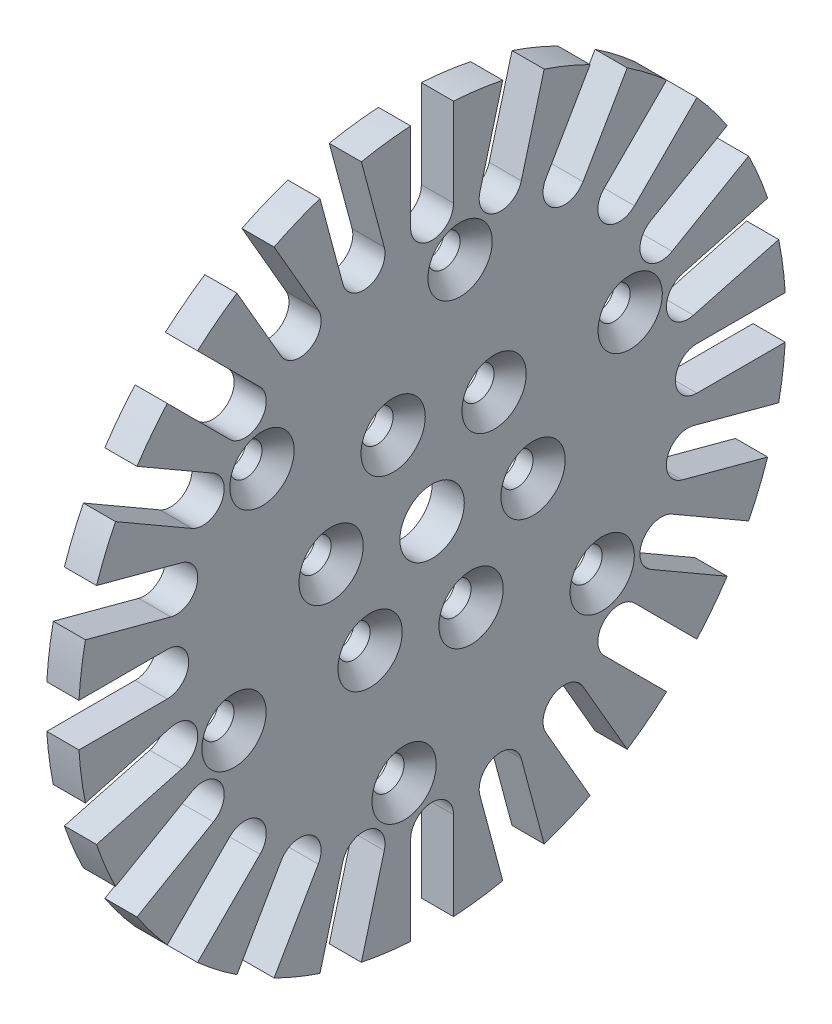
SolidWorks part; units mm, degrees
ref_plane "Front Plane" through (0, 0, 0) normal (0, 0, 1) x (1, 0, 0)
ref_plane "Top Plane" through (0, 0, 0) normal (0, 1, 0) x (1, 0, 0)
ref_plane "Right Plane" through (0, 0, 0) normal (1, 0, 0) x (0, 0, -1)
sketch "Sketch1" plane through (0, 0, 0) normal (1, 0, 0) x (0, 0, -1)
  circle A0 centre (0, 0) radius 33
  dimension "D1" = 66
extrude "Boss-Extrude1" add sketch "Sketch1" along normal blind 3
sketch "Sketch3" plane through (3, 0, 0) normal (1, 0, 0) x (0, 0, -1)
  circle A0 centre (0, 0) radius 3.005
  dimension "D1" = 6.01
extrude "Cut-Extrude2" cut sketch "Sketch3" against normal up to next
sketch "Sketch4" plane through (3, 0, 0) normal (1, 0, 0) x (0, 0, -1)
  line L0 (-2, 33) -> (-2, 24.7)
  line L1 (2, 24.7) -> (2, 33)
  line L2 (2, 33) -> (-2, 33)
  arc A0 (-2, 24.7) -> (2, 24.7) centre (0, 24.7) ccw
  circle A1 centre (0, 0) radius 33 construction
  dimension "D1" = 4
  dimension "D2" = 8.3
extrude "Cut-Extrude3" cut sketch "Sketch4" against normal up to next
pattern_circular "CirPattern2" count 24 over 360 about axis through (0, 0, 0) along (1, 0, 0) of "Cut-Extrude3"
sketch "Sketch2" plane through (3, 0, 0) normal (1, 0, 0) x (0, 0, -1)
  line L0 (2.6105, 19.8289) -> (0, 0) construction
  line L1 (0, 0) -> (3.005, 0) construction
  circle A0 centre (2.6105, 19.8289) radius 1.5
  circle A1 centre (0, 0) radius 3.005 construction
  dimension "D1" = 3
  dimension "D2" = 20
  dimension "D3" = 82.5
extrude "Cut-Extrude1" cut sketch "Sketch2" against normal up to next
chamfer "Chamfer1" distance 1.5 angle 45 1 edges at (3, 19.8289, -4.1105)
pattern_circular "CirPattern1" count 6 over 360 about axis through (0, 0, 0) along (1, 0, 0) of "Cut-Extrude1", "Chamfer1"
sketch "Sketch5" plane through (3, 0, 0) normal (1, 0, 0) x (0, 0, -1)
  line L0 (-3.6355, 8.7769) -> (0, 0) construction
  line L1 (0, 0) -> (-9.4948, 0) construction
  circle A0 centre (-3.6355, 8.7769) radius 1.5
  dimension "D1" = 3
  dimension "D2" = 9.5
  dimension "D3" = 67.5
extrude "Cut-Extrude4" cut sketch "Sketch5" against normal up to next
chamfer "Chamfer2" distance 1.5 angle 45 1 edges at (3, 8.7769, 2.1355)
pattern_circular "CirPattern3" count 6 over 360 about axis through (0, 0, 0) along (1, 0, 0) of "Cut-Extrude4", "Chamfer2"
